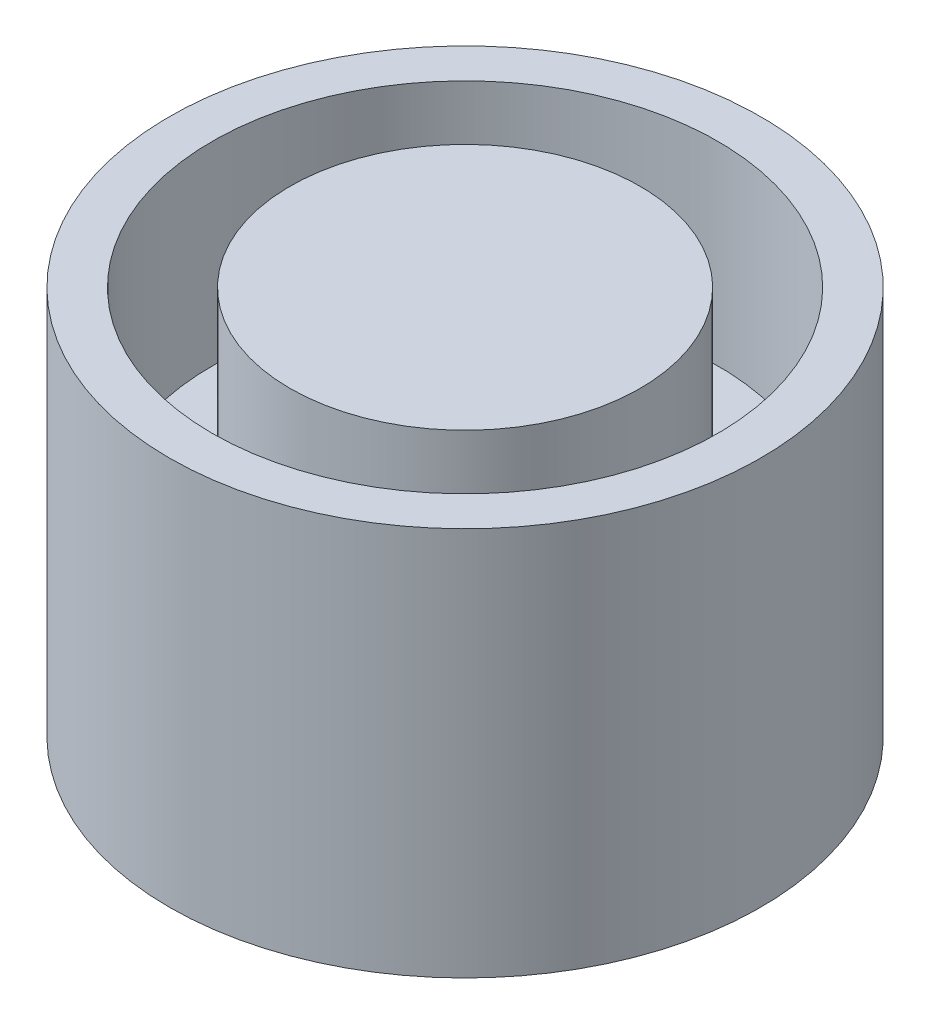
SolidWorks part; units mm, degrees
ref_plane "前视基准面" through (0, 0, 0) normal (0, 0, 1) x (1, 0, 0)
ref_plane "上视基准面" through (0, 0, 0) normal (0, 1, 0) x (1, 0, 0)
ref_plane "右视基准面" through (0, 0, 0) normal (1, 0, 0) x (0, 0, -1)
sketch "草图1" plane through (0, 0, 0) normal (0, 1, 0) x (1, 0, 0)
  circle A0 centre (0, 0) radius 7.6
  dimension "D1" = 15.2
extrude "凸台-拉伸1" add sketch "草图1" along normal blind 10
sketch "草图5" plane through (0, 10, 0) normal (0, 1, 0) x (1, 0, 0)
  circle A0 centre (0, 0) radius 4.5
  circle A1 centre (0, 0) radius 6.5
  dimension "D1" = 9
  dimension "D2" = 13
extrude "切除-拉伸1" cut sketch "草图5" against normal blind 5
